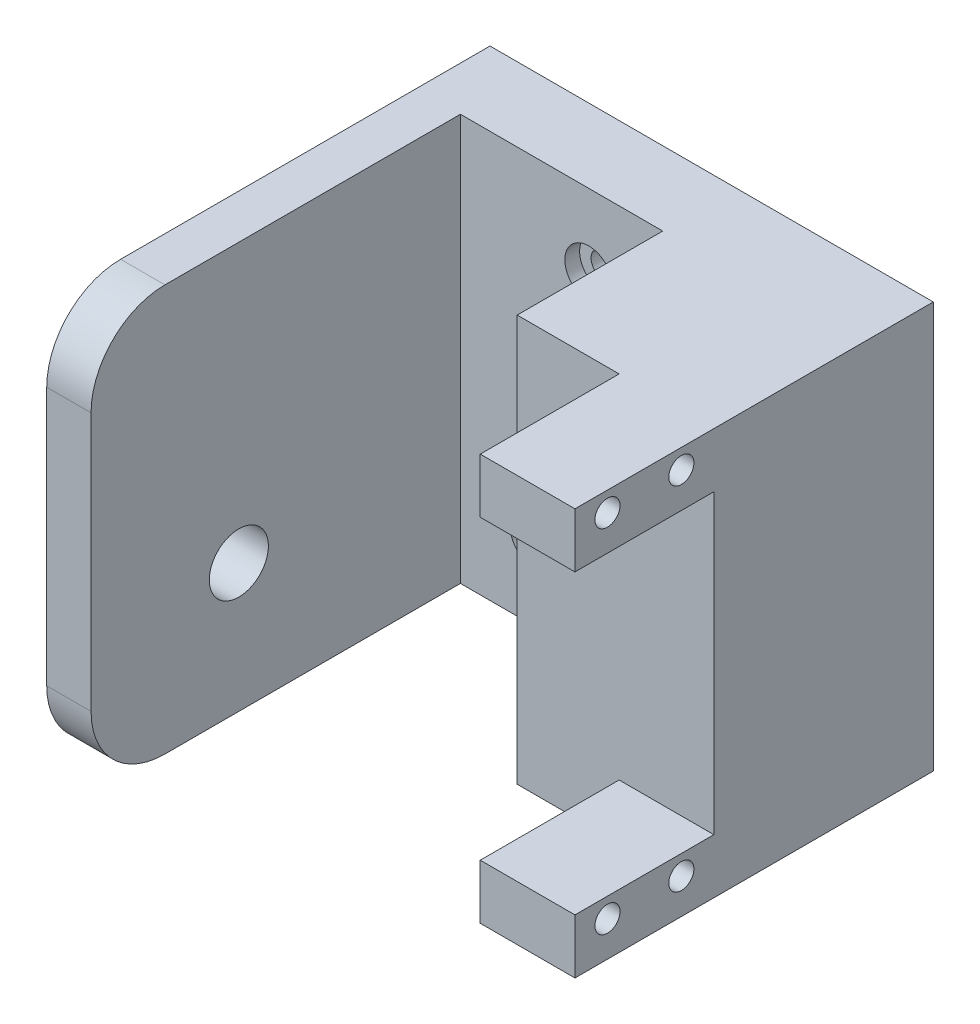
SolidWorks part; units mm, degrees
ref_plane "Plan de face" through (0, 0, 0) normal (0, 0, 1) x (1, 0, 0)
ref_plane "Plan de dessus" through (0, 0, 0) normal (0, 1, 0) x (1, 0, 0)
ref_plane "Plan de droite" through (0, 0, 0) normal (1, 0, 0) x (0, 0, -1)
sketch "Esquisse1" plane through (0, 0, 0) normal (0, 0, 1) x (1, 0, 0)
  line L1 (0, 0) -> (60, 0)
  line L2 (0, 0) -> (0, 55)
  line L3 (0, 55) -> (60, 55)
  line L4 (60, 0) -> (60, 55)
  dimension "D1" = 60
  dimension "D2" = 55
extrude "Boss.-Extru.1" add sketch "Esquisse1" along normal blind 10
sketch "Esquisse2" plane through (0, 0, 10) normal (0, 0, 1) x (1, 0, 0)
  line L0 (0, 0) -> (60, 0) construction
  line L1 (0, 55) -> (6, 55)
  line L2 (0, 55) -> (0, 0)
  line L3 (0, 0) -> (6, 0)
  line L4 (6, 55) -> (6, 0)
  dimension "D1" = 6
extrude "Boss.-Extru.2" add sketch "Esquisse2" along normal blind 50
sketch "Esquisse3" plane through (0, 0, 10) normal (0, 0, 1) x (1, 0, 0)
  line L0 (60, 55) -> (6, 55) construction
  line L1 (33.38, 55) -> (60, 55)
  line L2 (33.38, 55) -> (33.38, 0)
  line L3 (33.38, 0) -> (60, 0)
  line L4 (60, 55) -> (60, 0)
  line L5 (6, 0) -> (6, 55) construction
  dimension "D1" = 27.38
extrude "Boss.-Extru.3" add sketch "Esquisse3" along normal blind 19.7
sketch "Esquisse4" [suppressed] plane through (33.38, 0, 0) normal (-1, 0, 0) x (0, 0, 1)
  line L0 (29.7, 55) -> (10, 55) construction
  line L1 (29.7, 55) -> (29.7, 0) construction
  circle A0 centre (24.95, 45) radius 2.2
  circle A1 centre (24.95, 35) radius 2.2
  dimension "D3" = 4.4
  dimension "D4" = 4.4
  dimension "D1" = 10
  dimension "D2" = 10
  dimension "D5" = 4.75
  dimension "D6" = 4.75
hole_wizard "Dégagement M31" [suppressed] positions "Esquisse5" profile "Esquisse6" hole size "M3" standard "ISO"
sketch "Esquisse5" [suppressed] plane through (33.38, 0, 0) normal (-1, 0, 0) x (0, 0, 1)
  point P0 (24.95, 45)
  point P3 (24.95, 35)
sketch "Esquisse6" plane through (33.38, 45, 24.95) normal (0, 1, 0) x (0, 0, 1)
  line L0 (0, 0) -> (0, 27.6415)
  line L1 (0, 27.6415) -> (1.7, 26.62)
  line L2 (1.7, 26.62) -> (1.7, 0)
  line L5 (1.7, 0) -> (0, 0)
  line L10 (0, 27.6415) -> (-1.7, 26.62) construction
  line L11 (0, -6.35) -> (0, 107.95) construction
  dimension "Diamètre du perçage" = 3.4
  dimension "Profondeur du perçage" = 26.62
  dimension "Angle de pointe" = 118
sketch "Esquisse7" plane through (0, 0, 29.7) normal (0, 0, 1) x (1, 0, 0)
  line L0 (60, 55) -> (33.38, 55) construction
  line L1 (36.38, 48.05) -> (38.78, 48.05)
  line L2 (36.38, 48.05) -> (36.38, 41.95)
  line L3 (36.38, 41.95) -> (38.78, 41.95)
  line L4 (38.78, 48.05) -> (38.78, 41.95)
  line L5 (36.38, 13.05) -> (38.78, 13.05)
  line L6 (36.38, 13.05) -> (36.38, 6.95)
  line L7 (36.38, 6.95) -> (38.78, 6.95)
  line L8 (38.78, 13.05) -> (38.78, 6.95)
  line L9 (33.38, 55) -> (33.38, 0) construction
  line L10 (33.38, 0) -> (60, 0) construction
  point P8 (38.78, 45)
  point P11 (38.78, 10)
  dimension "D1" = 10
  dimension "D2" = 10
  dimension "D3" = 3
  dimension "D4" = 6.1
  dimension "D5" = 6.1
  dimension "D6" = 2.4
  dimension "D7" = 2.4
  dimension "D8" = 3
extrude "Enlèv. mat.-Extru.1" [suppressed] cut sketch "Esquisse7" against normal blind 8.45
sketch "Esquisse8" plane through (0, 0, 0) normal (-1, 0, 0) x (0, 0, 1)
  line L1 (0, 55) -> (0, 0) construction
  line L2 (60, 0) -> (0, 0) construction
  circle A0 centre (40, 17.4) radius 4
  dimension "D3" = 8
  dimension "D1" = 17.4
  dimension "D2" = 40
sketch "Esquisse9" plane through (0, 0, 10) normal (0, 0, 1) x (1, 0, 0)
  line L0 (33.38, 55) -> (33.38, 0) construction
  line L1 (33.38, 55) -> (6, 55) construction
  line L2 (6, 0) -> (6, 55) construction
  line L3 (6, 0) -> (33.38, 0) construction
  circle A0 centre (23.38, 45) radius 1.5
  circle A1 centre (16, 10) radius 1.5
  dimension "D5" = 3
  dimension "D6" = 3
  dimension "D1" = 10
  dimension "D2" = 10
  dimension "D3" = 10
  dimension "D4" = 10
hole_wizard "Chambrage pour tête cylindrique fendue M31" positions "Esquisse10" profile "Esquisse11" counterbore size "M3" standard "ISO"
sketch "Esquisse10" plane through (0, 0, 10) normal (0, 0, 1) x (1, 0, 0)
  point P0 (23.38, 45)
  point P3 (16, 10)
sketch "Esquisse11" plane through (23.38, 45, 10) normal (1, 0, 0) x (0, -1, 0)
  line L0 (0, 0) -> (0, 11.0215)
  line L1 (0, 11.0215) -> (1.7, 10)
  line L2 (1.7, 10) -> (1.7, 2)
  line L3 (1.7, 2) -> (3.25, 2)
  line L4 (3.25, 2) -> (3.25, 0)
  line L5 (3.25, 0) -> (0, 0)
  line L10 (0, 11.0215) -> (-1.7, 10) construction
  line L11 (0, -6.35) -> (0, 107.95) construction
  dimension "Diamètre du perçage" = 3.4
  dimension "Profondeur du perçage" = 10
  dimension "Diamètre du chambrage" = 6.5
  dimension "Profondeur du chambrage" = 2
  dimension "Angle de pointe" = 118
fillet "Congé1" radius 10 2 edges at (3, 55, 60) (3, 0, 60)
extrude "Enlèv. mat.-Extru.2" cut sketch "Esquisse8" against normal up to surface (6 mm away) up to face at (6, 27.5, 40.6904)
sketch "Esquisse12" plane through (0, 0, 29.7) normal (0, 0, 1) x (1, 0, 0)
  line L0 (60, 55) -> (33.38, 55) construction
  line L1 (47.18, 7.4) -> (60, 7.4)
  line L2 (47.18, 7.4) -> (47.18, 0)
  line L3 (47.18, 0) -> (60, 0)
  line L4 (60, 7.4) -> (60, 0)
  line L5 (47.18, 55) -> (60, 55)
  line L6 (47.18, 55) -> (47.18, 47.6)
  line L7 (47.18, 47.6) -> (60, 47.6)
  line L8 (60, 55) -> (60, 47.6)
  line L9 (33.38, 0) -> (60, 0) construction
  line L10 (33.38, 55) -> (33.38, 0) construction
  line L11 (33.38, 55) -> (33.38, 0) construction
  line L12 (60, 0) -> (60, 55) construction
  dimension "D1" = 7.4
  dimension "D2" = 7.4
  dimension "D5" = 13.8
  dimension "D6" = 13.8
extrude "Boss.-Extru.4" add sketch "Esquisse12" along normal blind 18.8
sketch "Esquisse13" plane through (47.18, 0, 0) normal (-1, 0, 0) x (0, 0, 1)
  line L0 (48.5, 55) -> (48.5, 47.6) construction
  line L1 (48.5, 47.6) -> (29.7, 47.6) construction
  line L2 (48.5, 7.4) -> (48.5, 0) construction
  line L3 (48.5, 0) -> (29.7, 0) construction
  circle A0 centre (44.1, 52.35) radius 1.5
  circle A1 centre (34.1, 52.35) radius 1.5
  circle A2 centre (44.1, 4.75) radius 1.5
  circle A3 centre (34.1, 4.75) radius 1.5
  dimension "D3" = 3
  dimension "D4" = 3
  dimension "D11" = 3
  dimension "D12" = 3
  dimension "D1" = 4.4
  dimension "D2" = 10
  dimension "D5" = 4.75
  dimension "D6" = 4.75
  dimension "D7" = 4.4
  dimension "D8" = 10
  dimension "D9" = 4.75
  dimension "D10" = 4.75
hole_wizard "Dégagement M32" positions "Esquisse18" profile "Esquisse19" hole size "M3" standard "ISO"
sketch "Esquisse18" plane through (47.18, 0, 0) normal (-1, 0, 0) x (0, 0, 1)
  point P0 (44.1, 52.35)
  point P3 (34.1, 52.35)
  point P6 (44.1, 4.75)
  point P9 (34.1, 4.75)
sketch "Esquisse19" plane through (47.18, 52.35, 44.1) normal (0, 1, 0) x (0, 0, 1)
  line L0 (0, 0) -> (0, 13.8415)
  line L1 (0, 13.8415) -> (1.7, 12.82)
  line L2 (1.7, 12.82) -> (1.7, 0)
  line L5 (1.7, 0) -> (0, 0)
  line L10 (0, 13.8415) -> (-1.7, 12.82) construction
  line L11 (0, -6.35) -> (0, 107.95) construction
  dimension "Diamètre du perçage" = 3.4
  dimension "Profondeur du perçage" = 12.82
  dimension "Angle de pointe" = 118
equation "\"D6@Esquisse4\"=\"D5@Esquisse4\""
